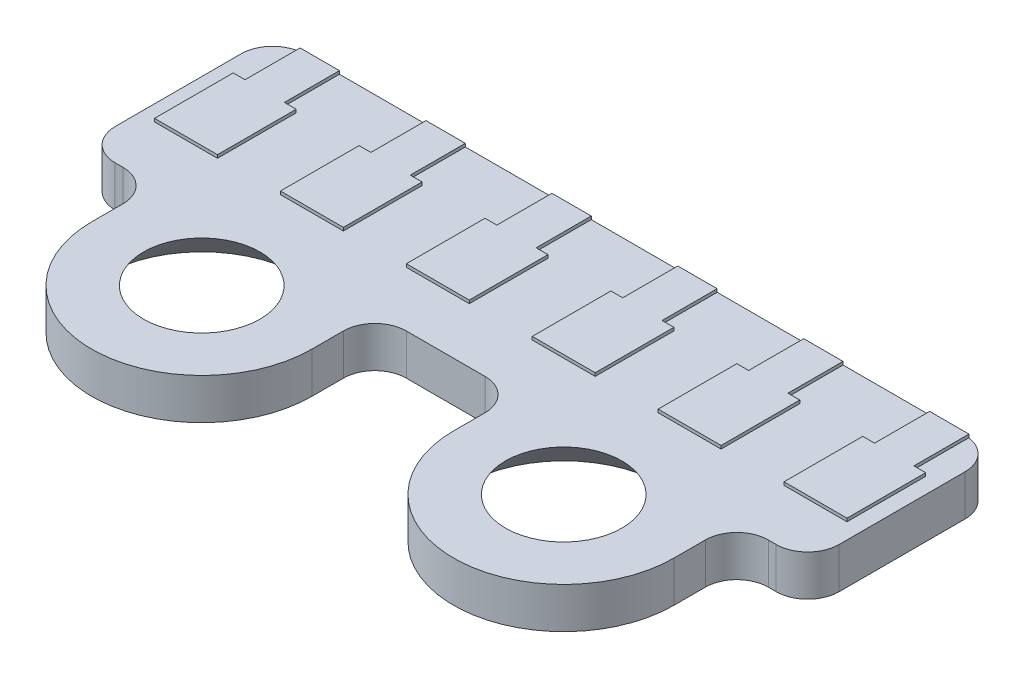
SolidWorks part; units mm, degrees
ref_plane "Front Plane" through (0, 0, 0) normal (0, 0, 1) x (1, 0, 0)
ref_plane "Top Plane" through (0, 0, 0) normal (0, 1, 0) x (1, 0, 0)
ref_plane "Right Plane" through (0, 0, 0) normal (1, 0, 0) x (0, 0, -1)
sketch "Sketch1" plane through (0, 0, 0) normal (0, 1, 0) x (1, 0, 0)
  line L0 (-11.5, 0) -> (0, 0) construction
  line L1 (-11.5, 3) -> (11.5, 3)
  line L2 (-11.5, 3) -> (-11.5, -3)
  line L4 (11.5, 3) -> (11.5, -3)
  line L5 (5.75, -5) -> (5.75, 0) construction
  line L6 (-11.5, -3) -> (-9.25, -3)
  line L7 (0, 0) -> (11.5, 0) construction
  line L8 (-5.75, 0) -> (-5.75, -5) construction
  line L9 (-9.25, -5) -> (-9.25, -3)
  line L16 (-2.25, -5) -> (-2.25, -3)
  line L17 (2.25, -5) -> (2.25, -3)
  line L18 (9.25, -5) -> (9.25, -3)
  line L19 (9.25, -3) -> (11.5, -3)
  line L20 (-2.25, -3) -> (2.25, -3)
  circle A4 centre (5.75, -5) radius 1.5
  circle A5 centre (-5.75, -5) radius 1.5
  arc A6 (2.25, -5) -> (9.25, -5) centre (5.75, -5) ccw
  arc A7 (-9.25, -5) -> (-2.25, -5) centre (-5.75, -5) ccw
  dimension "D3" = 7
  dimension "D5" = 3
  dimension "D1" = 23
  dimension "D2" = 6
  dimension "D6" = 5
extrude "Boss-Extrude1" add sketch "Sketch1" along normal blind 1.3
fillet "Fillet1" radius 1 8 edges at (11.5, 0.65, -3) (-11.5, 0.65, -3) (9.25, 0.65, 3) (-2.25, 0.65, 3) (11.5, 0.65, 3) (2.25, 0.65, 3) (-9.25, 0.65, 3) (-11.5, 0.65, 3)
sketch "Sketch5" plane through (0, 1.3, 0) normal (0, 1, 0) x (1, 0, 0)
  line L3 (-10, 0) -> (-6, 0) construction
  line L4 (-6, 0) -> (-2, 0) construction
  line L5 (-2, 0) -> (2, 0) construction
  line L6 (2, 0) -> (6, 0) construction
  line L7 (6, 0) -> (10, 0) construction
  line L10 (11.5, -2) -> (11.5, 2) construction
  line L11 (-10, 1.25) -> (-10, 3) construction
  line L12 (-11, -1.25) -> (-9, -1.25)
  line L13 (-11, -1.25) -> (-11, 1.25)
  line L14 (-11, 1.25) -> (-10.625, 1.25)
  line L15 (-9, -1.25) -> (-9, 1.25)
  line L16 (-11, -1.25) -> (-9, 1.25) construction
  line L17 (-11, 1.25) -> (-9, -1.25) construction
  line L18 (-7, -1.25) -> (-5, -1.25)
  line L19 (-7, -1.25) -> (-7, 1.25)
  line L20 (-7, 1.25) -> (-6.625, 1.25)
  line L21 (-5, -1.25) -> (-5, 1.25)
  line L22 (-7, -1.25) -> (-5, 1.25) construction
  line L23 (-7, 1.25) -> (-5, -1.25) construction
  line L24 (-3, -1.25) -> (-1, -1.25)
  line L25 (-3, -1.25) -> (-3, 1.25)
  line L26 (-3, 1.25) -> (-2.625, 1.25)
  line L27 (-1, -1.25) -> (-1, 1.25)
  line L28 (-3, -1.25) -> (-1, 1.25) construction
  line L29 (-3, 1.25) -> (-1, -1.25) construction
  line L30 (1, -1.25) -> (3, -1.25)
  line L31 (1, -1.25) -> (1, 1.25)
  line L32 (1, 1.25) -> (1.375, 1.25)
  line L33 (3, -1.25) -> (3, 1.25)
  line L34 (1, -1.25) -> (3, 1.25) construction
  line L35 (1, 1.25) -> (3, -1.25) construction
  line L36 (5, -1.25) -> (7, -1.25)
  line L37 (5, -1.25) -> (5, 1.25)
  line L38 (5, 1.25) -> (5.375, 1.25)
  line L39 (7, -1.25) -> (7, 1.25)
  line L40 (5, -1.25) -> (7, 1.25) construction
  line L41 (5, 1.25) -> (7, -1.25) construction
  line L42 (9, -1.25) -> (11, -1.25)
  line L43 (9, -1.25) -> (9, 1.25)
  line L44 (9, 1.25) -> (9.375, 1.25)
  line L45 (11, -1.25) -> (11, 1.25)
  line L46 (9, -1.25) -> (11, 1.25) construction
  line L47 (9, 1.25) -> (11, -1.25) construction
  line L48 (10.5, 3) -> (-10.5, 3) construction
  line L49 (-5.375, 1.25) -> (-5, 1.25)
  line L50 (-6, 1.25) -> (-6, 3) construction
  line L52 (-2, 1.25) -> (-2, 3) construction
  line L53 (-10.625, 1.25) -> (-10.625, 3)
  line L54 (2, 1.25) -> (2, 3) construction
  line L55 (-10.625, 3) -> (-9.375, 3)
  line L56 (6, 1.25) -> (6, 3) construction
  line L57 (-9.375, 1.25) -> (-9.375, 3)
  line L58 (10, 1.25) -> (10, 3) construction
  line L59 (-10.625, 1.25) -> (-9.375, 3) construction
  line L60 (-10.625, 3) -> (-9.375, 1.25) construction
  line L62 (-6.625, 1.25) -> (-6.625, 3)
  line L63 (-6.625, 3) -> (-5.375, 3)
  line L64 (-5.375, 1.25) -> (-5.375, 3)
  line L65 (-6.625, 1.25) -> (-5.375, 3) construction
  line L66 (-6.625, 3) -> (-5.375, 1.25) construction
  line L68 (-2.625, 1.25) -> (-2.625, 3)
  line L69 (-2.625, 3) -> (-1.375, 3)
  line L70 (-1.375, 1.25) -> (-1.375, 3)
  line L71 (-2.625, 1.25) -> (-1.375, 3) construction
  line L72 (-2.625, 3) -> (-1.375, 1.25) construction
  line L74 (1.375, 1.25) -> (1.375, 3)
  line L75 (1.375, 3) -> (2.625, 3)
  line L76 (2.625, 1.25) -> (2.625, 3)
  line L77 (1.375, 1.25) -> (2.625, 3) construction
  line L78 (1.375, 3) -> (2.625, 1.25) construction
  line L80 (5.375, 1.25) -> (5.375, 3)
  line L81 (5.375, 3) -> (6.625, 3)
  line L82 (6.625, 1.25) -> (6.625, 3)
  line L83 (5.375, 1.25) -> (6.625, 3) construction
  line L84 (5.375, 3) -> (6.625, 1.25) construction
  line L86 (9.375, 1.25) -> (9.375, 3)
  line L87 (9.375, 3) -> (10.625, 3)
  line L88 (10.625, 1.25) -> (10.625, 3)
  line L89 (9.375, 1.25) -> (10.625, 3) construction
  line L90 (9.375, 3) -> (10.625, 1.25) construction
  line L91 (-1.375, 1.25) -> (-1, 1.25)
  line L92 (2.625, 1.25) -> (3, 1.25)
  line L93 (6.625, 1.25) -> (7, 1.25)
  line L94 (10.625, 1.25) -> (11, 1.25)
  line L95 (-9.375, 1.25) -> (-9, 1.25)
  point P52 (-10, 2.125)
  point P57 (-6, 2.125)
  point P62 (-2, 2.125)
  point P67 (2, 2.125)
  point P72 (6, 2.125)
  point P77 (10, 2.125)
  dimension "D1" = 4
  dimension "D2" = 2.5
  dimension "D3" = 2
  dimension "D4" = 1.25
extrude "Boss-Extrude3" add sketch "Sketch5" along normal blind 0.1 and the other way blind 1.4
hole_wizard "CSK for M3 Flat Head Machine Screw2" positions "Sketch6" profile "Sketch7" countersink size "M3" standard "ANSI Metric" end condition through all
sketch "Sketch6" plane through (0, 0, 0) normal (0, -1, 0) x (-1, 0, 0)
  point P0 (-5.75, -5)
  point P3 (5.75, -5)
sketch "Sketch7" plane through (5.75, 0, 5) normal (1, 0, 0) x (0, 0, -1)
  line L0 (0, 0) -> (0, 1.4)
  line L1 (0, 1.4) -> (1.7, 1.4)
  line L2 (1.7, 1.4) -> (1.7, 1.45)
  line L3 (1.7, 1.45) -> (3.15, 0)
  line L5 (3.15, 0) -> (0, 0)
  line L6 (-1.7, 1.45) -> (-3.15, 0) construction
  line L11 (0, -6.35) -> (0, 107.95) construction
  dimension "Thru Hole Dia." = 3.4
  dimension "Thru Hole Depth" = 1.4
  dimension "Near C'Sink Dia." = 6.3
  dimension "Near C'Sink Angle" = 90
